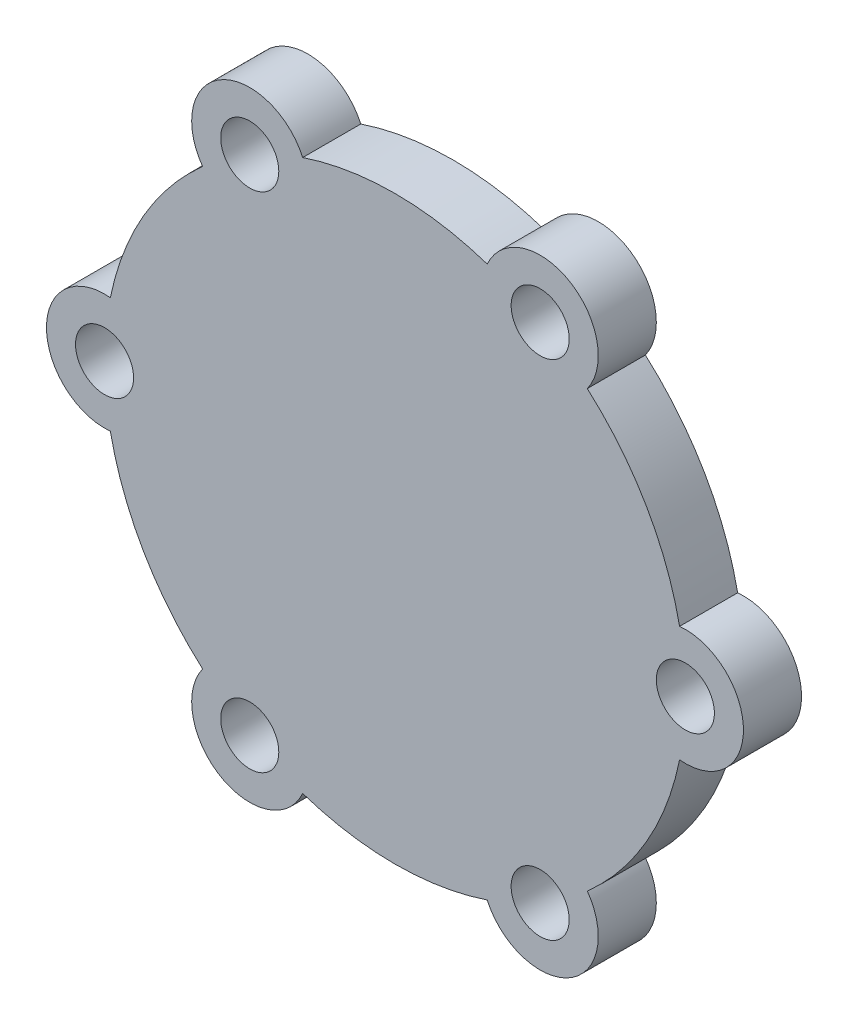
SolidWorks part; units mm, degrees
ref_plane "Front Plane" through (0, 0, 0) normal (0, 0, 1) x (1, 0, 0)
ref_plane "Top Plane" through (0, 0, 0) normal (0, 1, 0) x (1, 0, 0)
ref_plane "Right Plane" through (0, 0, 0) normal (1, 0, 0) x (0, 0, -1)
sketch "Sketch2" plane through (0, 0, 0) normal (0, 0, 1) x (1, 0, 0)
  line L0 (0, 0) -> (0, 41444.4653) construction
  line L1 (0, 0) -> (41444.4653, 0) construction
  arc A0 (49, 9.9499) -> (33.1168, 37.4603) centre (0, 0) ccw
  arc A1 (49, -9.9499) -> (49, 9.9499) centre (50, 0) ccw
  circle A2 centre (50, 0) radius 5
  arc A3 (-33.1168, 37.4603) -> (-49, 9.9499) centre (0, 0) ccw
  arc A4 (15.8832, -47.4102) -> (33.1168, -37.4603) centre (25, -43.3013) ccw
  circle A5 centre (25, -43.3013) radius 5
  arc A6 (-33.1168, -37.4603) -> (-15.8832, -47.4102) centre (-25, -43.3013) ccw
  circle A7 centre (-25, -43.3013) radius 5
  arc A8 (-49, 9.9499) -> (-49, -9.9499) centre (-50, 0) ccw
  circle A9 centre (-50, 0) radius 5
  arc A10 (-15.8832, 47.4102) -> (-33.1168, 37.4603) centre (-25, 43.3013) ccw
  circle A11 centre (-25, 43.3013) radius 5
  arc A12 (33.1168, 37.4603) -> (15.8832, 47.4102) centre (25, 43.3013) ccw
  circle A13 centre (25, 43.3013) radius 5
  arc A14 (-15.8832, -47.4102) -> (15.8832, -47.4102) centre (0, 0) ccw
  arc A15 (-49, -9.9499) -> (-33.1168, -37.4603) centre (0, 0) ccw
  arc A16 (33.1168, -37.4603) -> (49, -9.9499) centre (0, 0) ccw
  arc A17 (15.8832, 47.4102) -> (-15.8832, 47.4102) centre (0, 0) ccw
  point P34 (0, 0)
  dimension "D1" = 100
  dimension "D2" = 20
  dimension "D3" = 10
  dimension "D4" = 6
extrude "Boss-Extrude1" add sketch "Sketch2" along normal blind 10
